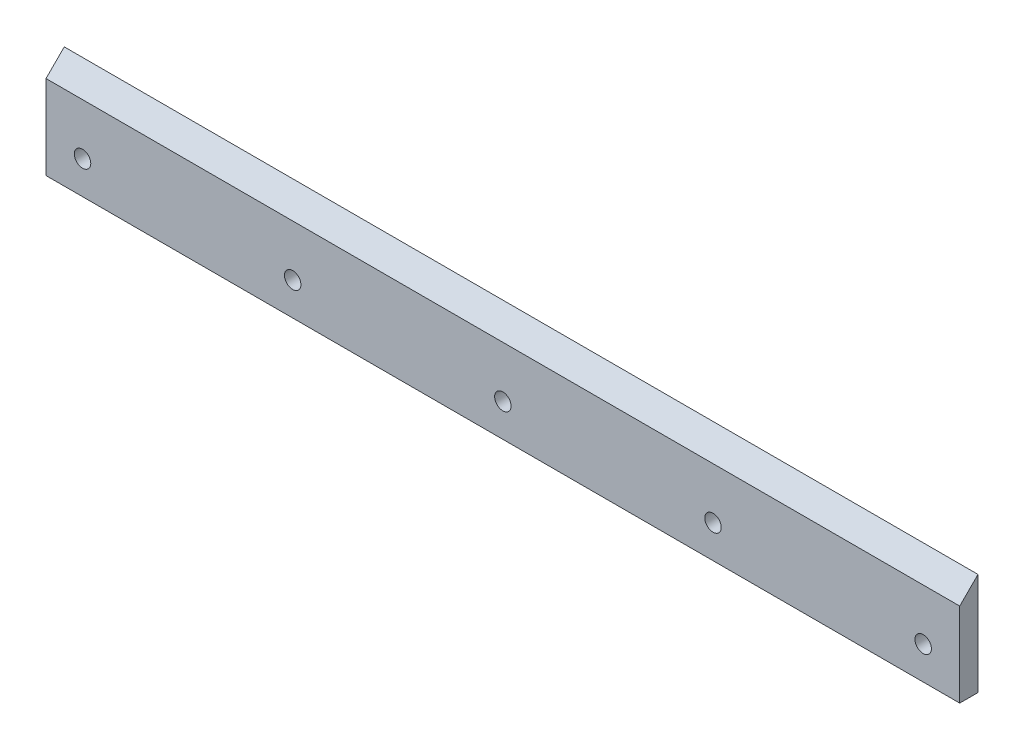
SolidWorks part; units mm, degrees
ref_plane "Front" through (0, 0, 0) normal (0, 0, 1) x (1, 0, 0)
ref_plane "Top" through (0, 0, 0) normal (0, 1, 0) x (1, 0, 0)
ref_plane "Right" through (0, 0, 0) normal (1, 0, 0) x (0, 0, -1)
sketch "Sketch1" plane through (0, 0, 0) normal (1, 0, 0) x (0, 0, -1)
  line L0 (-5, 23) -> (0, 28)
  line L1 (0, 0) -> (-5, 0)
  line L2 (0, 0) -> (0, 28)
  line L4 (-5, 0) -> (-5, 23)
  dimension "D1" = 5
  dimension "D2" = 28
  dimension "D3" = 23
extrude "Boss-Extrude1" add sketch "Sketch1" along normal blind 250
hole_wizard "M4 Clearance Hole1" positions "Sketch2" profile "Sketch3" hole size "M4" standard "JIS" end condition through all
sketch "Sketch2" plane through (0, 0, 5) normal (0, 0, 1) x (1, 0, 0)
  line L1 (250, 0) -> (0, 0) construction
  line L2 (0, 23) -> (0, 0) construction
  point P0 (10, 9)
  dimension "D1" = 10
  dimension "D2" = 9
sketch "Sketch3" plane through (10, 9, 5) normal (1, 0, 0) x (0, -1, 0)
  line L0 (0, 0) -> (0, 5)
  line L1 (0, 5) -> (2.25, 5)
  line L2 (2.25, 5) -> (2.25, 0)
  line L5 (2.25, 0) -> (0, 0)
  line L11 (0, -6.35) -> (0, 107.95) construction
  dimension "通し穴の直径" = 4.5
  dimension "通し穴の深さ" = 5
pattern_linear "LPattern1" count 5 spacing 57.5 along (1, 0, 0) of "M4 Clearance Hole1"
